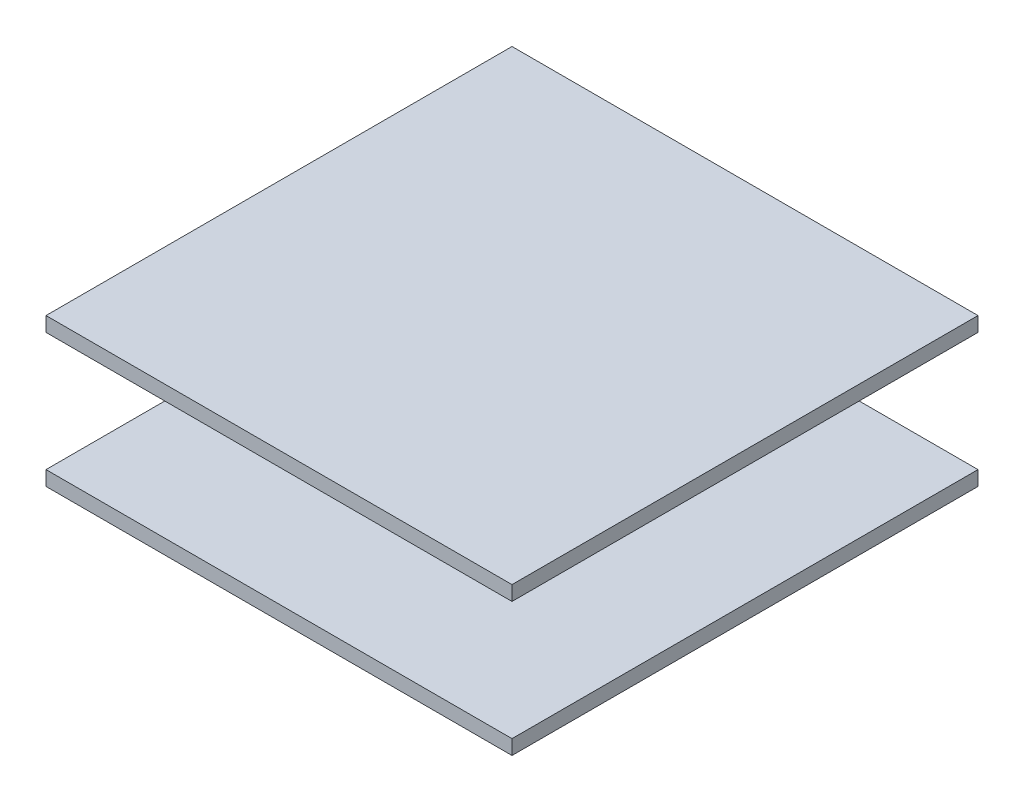
SolidWorks part; units mm, degrees
ref_plane "Front Plane" through (0, 0, 0) normal (0, 0, 1) x (1, 0, 0)
ref_plane "Top Plane" through (0, 0, 0) normal (0, 1, 0) x (1, 0, 0)
ref_plane "Right Plane" through (0, 0, 0) normal (1, 0, 0) x (0, 0, -1)
sketch "Sketch2" plane through (0, 0, 0) normal (0, 1, 0) x (1, 0, 0)
  line L1 (-25.5, -25.5) -> (25.5, -25.5)
  line L2 (-25.5, -25.5) -> (-25.5, 25.5)
  line L3 (-25.5, 25.5) -> (25.5, 25.5)
  line L4 (25.5, -25.5) -> (25.5, 25.5)
  line L5 (-25.5, -25.5) -> (25.5, 25.5) construction
  line L6 (-25.5, 25.5) -> (25.5, -25.5) construction
  point P0 (0, 0)
  dimension "D1" = 51
extrude "Boss-Extrude1" add sketch "Sketch2" against normal blind 1.6
sketch "Sketch4" plane through (0, 0, 0) normal (0, 1, 0) x (1, 0, 0)
  line L4 (25.5, -25.5) -> (25.5, 25.5)
  line L5 (25.5, 25.5) -> (-25.5, 25.5)
  line L6 (-25.5, 25.5) -> (-25.5, -25.5)
  line L7 (-25.5, -25.5) -> (25.5, -25.5)
  line L8 (25.5, -25.5) -> (25.5, 25.5)
  line L9 (25.5, 25.5) -> (-25.5, 25.5)
  line L10 (-25.5, 25.5) -> (-25.5, -25.5)
  line L11 (-25.5, -25.5) -> (25.5, -25.5)
  dimension "D1" = 0
extrude "Boss-Extrude2" add sketch "Sketch4" along normal blind 1.6 from offset 13 separate body
